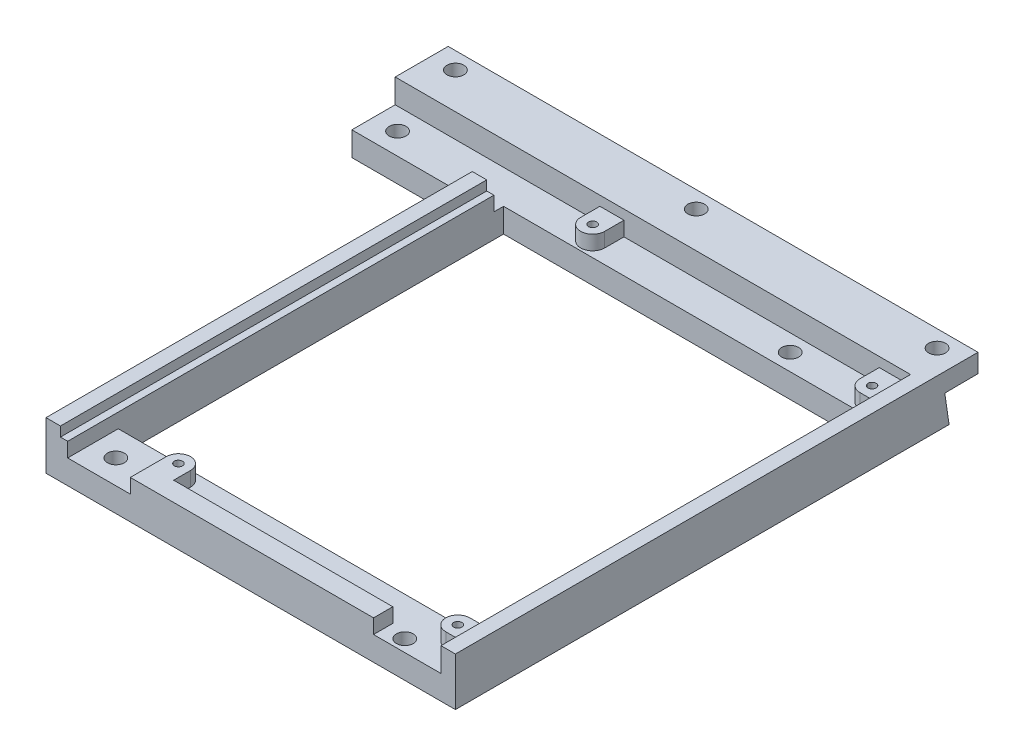
SolidWorks part; units mm, degrees
ref_plane "정면" through (0, 0, 0) normal (0, 0, 1) x (1, 0, 0)
ref_plane "윗면" through (0, 0, 0) normal (0, 1, 0) x (1, 0, 0)
ref_plane "우측면" through (0, 0, 0) normal (1, 0, 0) x (0, 0, -1)
sketch "스케치2" plane through (0, 0, 0) normal (0, 1, 0) x (1, 0, 0)
  line L1 (-55, 54.25) -> (55, 54.25)
  line L2 (-55, 54.25) -> (-55, -54.25)
  line L3 (-55, -54.25) -> (55, -54.25)
  line L4 (55, 54.25) -> (55, -54.25)
  line L5 (-55, 54.25) -> (55, -54.25) construction
  line L6 (-55, -54.25) -> (55, 54.25) construction
  point P0 (0, 0)
  dimension "D1" = 110
  dimension "D2" = 108.5
extrude "보스-돌출1" add sketch "스케치2" along normal blind 10
sketch "스케치3" plane through (-55, 0, 0) normal (-1, 0, 0) x (0, 0, 1)
  line L0 (-54.25, 6.15) -> (-47.3512, 6.1048)
  line L1 (-54.25, 0) -> (-48.25, 0)
  line L2 (-54.25, 0) -> (-54.25, 6.15)
  line L4 (-48.25, 0) -> (-47.3512, 6.1048)
  dimension "D1" = 6.15
  dimension "D2" = 6
  dimension "D3" = 82
extrude "컷-돌출1" cut sketch "스케치3" against normal through all
sketch "스케치4" plane through (0, 10, 0) normal (0, 1, 0) x (1, 0, 0)
  line L0 (-55, 54.25) -> (-55, -54.25) construction
  line L5 (-55, 34.25) -> (-30, 34.25)
  line L6 (-55, 34.25) -> (-55, -54.25)
  line L7 (-55, -54.25) -> (-30, -54.25)
  line L8 (-30, 34.25) -> (-30, -54.25)
  line L9 (-55, -54.25) -> (55, -54.25) construction
  line L10 (55, 54.25) -> (-55, 54.25) construction
  dimension "D3" = 20
  dimension "D4" = 25
extrude "컷-돌출2" cut sketch "스케치4" against normal through all
sketch "스케치5" plane through (0, 10, 0) normal (0, 1, 0) x (1, 0, 0)
  line L0 (-55, 54.25) -> (-55, 34.25) construction
  line L1 (52, -54.25) -> (-27, -54.25)
  line L2 (52, -54.25) -> (52, 43.25)
  line L3 (52, 43.25) -> (-55, 43.25)
  line L4 (-55, 34.25) -> (-55, 43.25)
  line L5 (55, -54.25) -> (55, 54.25) construction
  line L6 (55, 54.25) -> (-55, 54.25) construction
  line L7 (-30, -54.25) -> (-30, 34.25) construction
  line L10 (-55, 34.25) -> (-27, 34.25)
  line L11 (-27, -54.25) -> (-27, 34.25)
  line L12 (-30, 34.25) -> (-55, 34.25) construction
  line L13 (-30, -54.25) -> (55, -54.25) construction
  dimension "D1" = 3
  dimension "D2" = 11
  dimension "D3" = 3
extrude "컷-돌출3" cut sketch "스케치5" against normal blind 2
sketch "스케치6" plane through (0, 8, 0) normal (0, 1, 0) x (1, 0, 0)
  line L0 (52, 43.25) -> (-55, 43.25) construction
  line L1 (-25.5, -43.75) -> (50.5, -43.75)
  line L2 (-25.5, -43.75) -> (-25.5, 36.25)
  line L3 (-25.5, 36.25) -> (50.5, 36.25)
  line L4 (50.5, -43.75) -> (50.5, 36.25)
  line L5 (52, -54.25) -> (52, 43.25) construction
  line L7 (-27, 34.25) -> (-27, -54.25) construction
  dimension "D1" = 1.5
  dimension "D3" = 7
  dimension "D4" = 1.5
extrude "컷-돌출4" cut sketch "스케치6" against normal through all
sketch "스케치7" plane through (0, 8, 0) normal (0, 1, 0) x (1, 0, 0)
  line L0 (52, -54.25) -> (38, -54.25)
  line L2 (52, -54.25) -> (52, -49.25)
  line L4 (-25.5, -54.25) -> (-25.5, 34.25)
  line L5 (-12.5, -54.25) -> (-25.5, -54.25)
  line L6 (-55, 34.25) -> (-25.5, 34.25)
  line L7 (-55, 34.25) -> (-55, 43.25)
  line L10 (-10, 39.25) -> (48, 39.25) construction
  line L11 (-10, 39.25) -> (-10, -46.75) construction
  line L12 (-10, -46.75) -> (48, -46.75) construction
  line L13 (48, 39.25) -> (48, -46.75) construction
  line L15 (-7.5, 39.25) -> (-7.5, 43.25)
  line L17 (-12.5, 39.25) -> (-12.5, 43.25)
  line L21 (45.5, 39.25) -> (45.5, 43.25)
  line L27 (-7.5, -46.75) -> (-7.5, -50.25)
  line L29 (-12.5, -46.75) -> (-12.5, -54.25)
  line L30 (-12.5, 43.25) -> (-55, 43.25)
  line L31 (45.5, 43.25) -> (-7.5, 43.25)
  line L33 (48, -44.25) -> (50.5, -44.25)
  line L35 (48, -49.25) -> (52, -49.25)
  line L37 (-25.5, 36.25) -> (-25.5, -43.75) construction
  line L40 (50.5, 36.75) -> (50.5, -44.25)
  line L41 (48, 36.75) -> (50.5, 36.75)
  line L43 (-27, -54.25) -> (52, -54.25) construction
  line L46 (-7.5, -50.25) -> (38, -50.25)
  line L47 (38, -54.25) -> (38, -50.25)
  arc A0 (-12.5, 39.25) -> (-7.5, 39.25) centre (-10, 39.25) ccw
  arc A1 (45.5, 39.25) -> (48, 36.75) centre (48, 39.25) ccw
  arc A3 (-7.5, -46.75) -> (-12.5, -46.75) centre (-10, -46.75) ccw
  arc A4 (48, -44.25) -> (48, -49.25) centre (48, -46.75) ccw
  dimension "D5" = 5
  dimension "D3" = 2.5
  dimension "D1" = 58
  dimension "D2" = 86
  dimension "D4" = 4
  dimension "D6" = 14
  dimension "D7" = 4
extrude "컷-돌출5" cut sketch "스케치7" against normal blind 3
sketch "스케치8" plane through (0, 8, 0) normal (0, 1, 0) x (1, 0, 0)
  line L0 (-25.5, -43.75) -> (-25.5, -54.25) construction
  line L2 (-25.5, -54.25) -> (-12.5, -54.25) construction
  line L3 (-55, 43.25) -> (-55, 34.25) construction
  line L4 (-55, 34.25) -> (-30, 34.25) construction
  line L5 (-25.5, 36.25) -> (50.5, 36.25) construction
  line L6 (45.5, 39.25) -> (45.5, 43.25) construction
  line L7 (52, -49.25) -> (48, -49.25) construction
  line L8 (52, -54.25) -> (52, -49.25) construction
  circle A0 centre (-10, 39.25) radius 0.85
  circle A1 centre (48, 39.25) radius 0.85
  circle A2 centre (-10, -46.75) radius 0.85
  circle A3 centre (48, -46.75) radius 0.85
  circle A4 centre (-50, 38.75) radius 1.75
  circle A5 centre (30.5, 39.75) radius 1.75
  circle A6 centre (42, -51.75) radius 1.75
  circle A7 centre (-20.5, -49.25) radius 1.75
  dimension "D1" = 1.7
  dimension "D2" = 3.5
  dimension "D4" = 5
  dimension "D5" = 5
  dimension "D6" = 4.5
  dimension "D7" = 3.5
  dimension "D8" = 15
  dimension "D9" = 2.5
  dimension "D10" = 10
  dimension "D3" = 5
extrude "컷-돌출6" cut sketch "스케치8" against normal through all
sketch "스케치9" plane through (0, 10, 0) normal (0, 1, 0) x (1, 0, 0)
  line L0 (-55, 50.75) -> (55, 50.75) construction
  line L1 (-55, 54.25) -> (-55, 43.25) construction
  line L2 (55, -54.25) -> (55, 54.25) construction
  line L3 (55, 54.25) -> (-55, 54.25) construction
  circle A0 centre (-50, 50.75) radius 1.75
  circle A1 centre (0, 50.75) radius 1.75
  circle A2 centre (50, 50.75) radius 1.75
  dimension "D1" = 3.5
  dimension "D3" = 5
  dimension "D4" = 5
  dimension "D2" = 3.5
extrude "컷-돌출7" cut sketch "스케치9" against normal through all
